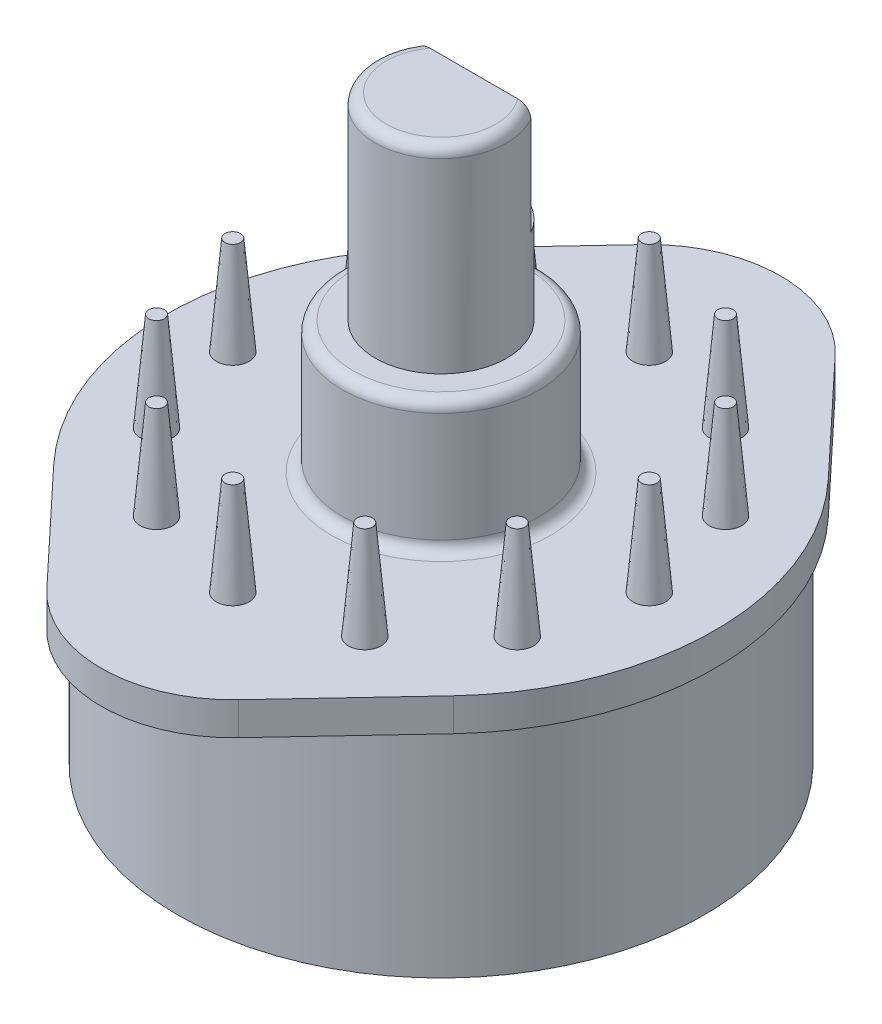
SolidWorks part; units mm, degrees
ref_plane "Front" through (0, 0, 0) normal (0, 0, 1) x (1, 0, 0)
ref_plane "Top" through (0, 0, 0) normal (0, 1, 0) x (1, 0, 0)
ref_plane "Right" through (0, 0, 0) normal (1, 0, 0) x (0, 0, -1)
sketch "Sketch1" plane through (0, 0, 0) normal (1, 0, 0) x (0, 0, -1)
  line L0 (0, 0) -> (0, 43256.3119) construction
  line L4 (4.5, 17.5) -> (4.5, 11.5)
  line L5 (4.5, 11.5) -> (12, 11.5)
  line L8 (12, 11.5) -> (12, 0)
  line L10 (0, 26.5) -> (0, 0)
  line L13 (0, 26.5) -> (3, 26.5)
  line L14 (3, 26.5) -> (3, 17.5)
  line L15 (3, 17.5) -> (4.5, 17.5)
  line L16 (12, 0) -> (6, 0)
  line L17 (6, 0) -> (6, -3)
  line L18 (6, -3) -> (0, -3)
  line L19 (0, 0) -> (0, -3)
  dimension "D1" = 6
  dimension "D2" = 15
  dimension "D3" = 6
  dimension "D4" = 11.5
  dimension "D5" = 9
  dimension "D6" = 3
  dimension "D7" = 12
  dimension "D8" = 24
revolve "Revolve1" add sketch "Sketch1" angle 360 about L0
sketch "Sketch2" plane through (0, 26.5, 0) normal (0, 1, 0) x (1, 0, 0)
  line L0 (2.5981, 1.5) -> (-2.5981, 1.5)
  circle A0 centre (0, 0) radius 3 construction
  arc A1 (2.5981, 1.5) -> (-2.5981, 1.5) centre (0, 0) ccw
  dimension "D1" = 1.5
extrude "Cut-Extrude1" cut sketch "Sketch2" against normal blind 5
fillet "Fillet1" radius 0.5 4 edges at (0, 11.5, -4.5) (0, 17.5, -4.5) (0, 26.5, 3) (0, -3, -6)
sketch "Sketch3" plane through (0, 11.5, 0) normal (0, 1, 0) x (1, 0, 0)
  line L0 (0, -15.5) -> (0, 15.5) construction
  line L1 (-9.1161, 8.5526) -> (-4.3757, 13.6053)
  line L2 (4.3757, 13.6053) -> (9.1161, 8.5526)
  line L3 (-9.1161, -8.5526) -> (-4.3757, -13.6053)
  line L4 (9.1161, -8.5526) -> (4.3757, -13.6053)
  circle A0 centre (0, 0) radius 12.5 construction
  arc A1 (-4.3757, 13.6053) -> (4.3757, 13.6053) centre (0, 9.5) cw
  arc A2 (-4.3757, -13.6053) -> (4.3757, -13.6053) centre (0, -9.5) ccw
  arc A3 (-9.1161, 8.5526) -> (-9.1161, -8.5526) centre (0, 0) ccw
  arc A4 (9.1161, 8.5526) -> (9.1161, -8.5526) centre (0, 0) cw
  point P6 (0, 0)
  point P19 (0, -15.5)
  dimension "D2" = 25
  dimension "D3" = 6
  dimension "D1" = 31
extrude "Boss-Extrude1" add sketch "Sketch3" against normal blind 1.5
sketch "Sketch4" plane through (0, 11.5, 0) normal (0, 1, 0) x (1, 0, 0)
  circle A0 centre (0, 0) radius 9.5 construction
  circle A1 centre (0, -9.5) radius 0.75
  circle A2 centre (-4.75, -8.2272) radius 0.75
  circle A3 centre (-8.2272, -4.75) radius 0.75
  circle A4 centre (-9.5, 0) radius 0.75
  circle A5 centre (-8.2272, 4.75) radius 0.75
  circle A6 centre (-4.75, 8.2272) radius 0.75
  circle A7 centre (0, 9.5) radius 0.75
  circle A8 centre (4.75, 8.2272) radius 0.75
  circle A9 centre (8.2272, 4.75) radius 0.75
  circle A10 centre (9.5, 0) radius 0.75
  circle A11 centre (8.2272, -4.75) radius 0.75
  circle A12 centre (4.75, -8.2272) radius 0.75
  point P29 (0, 0)
  dimension "D1" = 19
  dimension "D2" = 1.5
  dimension "D3" = 12
extrude "Boss-Extrude2" add sketch "Sketch4" along normal blind 4.5 draft 5
